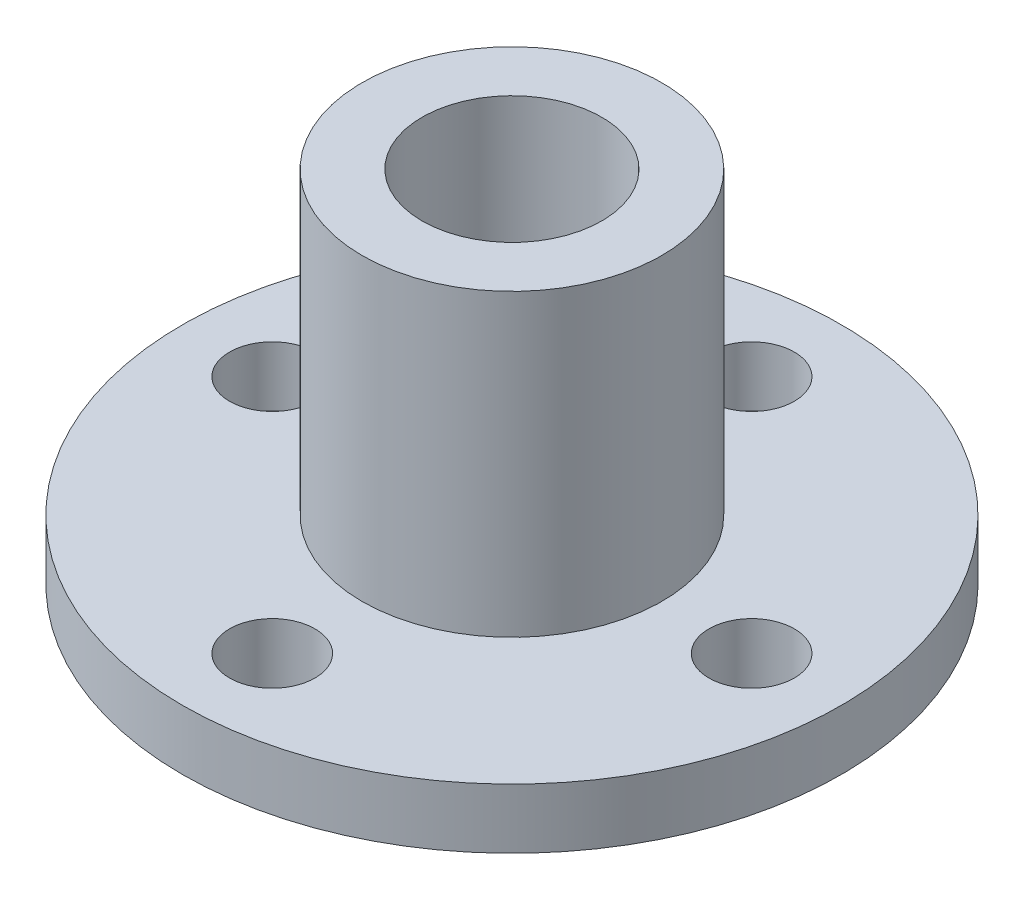
SolidWorks part; units mm, degrees
ref_plane "Front Plane" through (0, 0, 0) normal (0, 0, 1) x (1, 0, 0)
ref_plane "Top Plane" through (0, 0, 0) normal (0, 1, 0) x (1, 0, 0)
ref_plane "Right Plane" through (0, 0, 0) normal (1, 0, 0) x (0, 0, -1)
sketch "Sketch1" plane through (0, 0, 0) normal (0, 1, 0) x (1, 0, 0)
  circle A0 centre (0, 0) radius 11
  dimension "D1" = 22
extrude "Boss-Extrude1" add sketch "Sketch1" along normal blind 2
sketch "Sketch2" plane through (0, 2, 0) normal (0, 1, 0) x (1, 0, 0)
  circle A0 centre (0, 0) radius 5
  dimension "D1" = 10
extrude "Boss-Extrude2" add sketch "Sketch2" along normal blind 10
sketch "Sketch3" plane through (0, 12, 0) normal (0, 1, 0) x (1, 0, 0)
  circle A0 centre (0, 0) radius 3
  dimension "D1" = 6
extrude "Cut-Extrude1" cut sketch "Sketch3" against normal through all
sketch "Sketch4" plane through (0, 2, 0) normal (0, 1, 0) x (1, 0, 0)
  circle A0 centre (0, 8) radius 1.425
  circle A1 centre (8, 0) radius 1.425
  circle A2 centre (0, -8) radius 1.425
  circle A3 centre (-8, 0) radius 1.425
  point P12 (0, 0)
  dimension "D1" = 2.85
  dimension "D2" = 8
  dimension "D3" = 4
extrude "Cut-Extrude2" cut sketch "Sketch4" against normal through all
